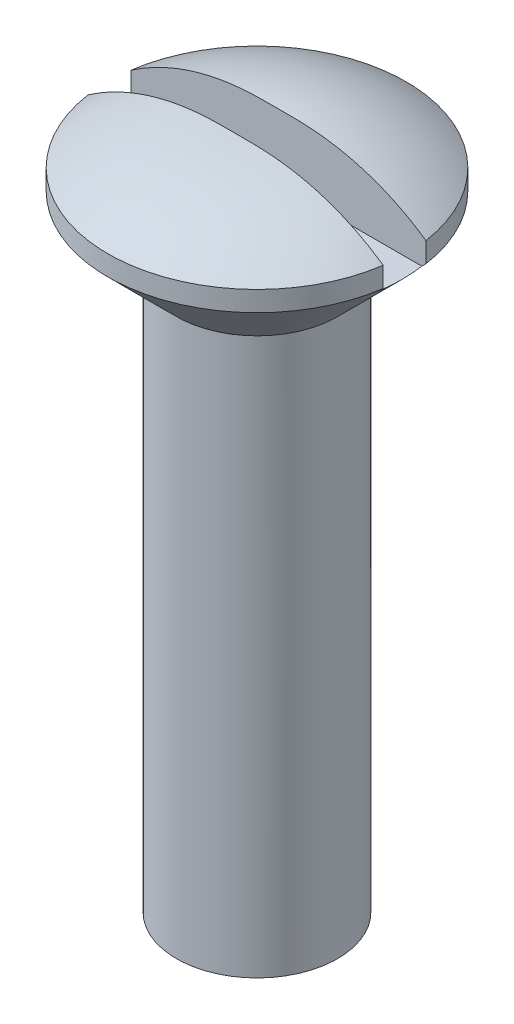
SolidWorks part; units mm, degrees
ref_plane "Спереди" through (0, 0, 0) normal (0, 0, 1) x (1, 0, 0)
ref_plane "Сверху" through (0, 0, 0) normal (0, 1, 0) x (1, 0, 0)
ref_plane "Справа" through (0, 0, 0) normal (1, 0, 0) x (0, 0, -1)
sketch "Эскиз1" plane through (0, 0, 0) normal (0, 0, 1) x (1, 0, 0)
  line L0 (0, 0) -> (0, 8.0477) construction
  line L1 (0, 0) -> (2, 0)
  line L2 (2, 0) -> (2, 13.8)
  line L3 (2, 13.8) -> (3.7, 15.5)
  line L4 (3.7, 15.5) -> (3.7, 16)
  line L5 (0, 17) -> (0.53, 17)
  line L6 (0, 0) -> (0, 17)
  arc A0 (0.53, 17) -> (3.7, 16) centre (0.53, 11.4756) cw
  dimension "D1" = 4
  dimension "D2" = 45
  dimension "D3" = 7.4
  dimension "D4" = 2.2
  dimension "D5" = 16
  dimension "D6" = 1
  dimension "D7" = 1.06
revolve "Основание-Повернуть" add sketch "Эскиз1" angle 360 about L0
sketch "Эскиз2" plane through (0, 17, 0) normal (0, 1, 0) x (-1, 0, 0)
  line L0 (-3.6618, -0.53) -> (3.6618, -0.53)
  line L1 (-3.6618, 0.53) -> (3.6618, 0.53)
  circle A0 centre (0, 0) radius 3.7 construction
  arc A1 (-3.6618, 0.53) -> (-3.6618, -0.53) centre (0, 0) ccw
  circle A2 centre (0, 0) radius 0.53 construction
  arc A3 (3.6618, -0.53) -> (3.6618, 0.53) centre (0, 0) ccw
extrude "Вырез-Вытянуть1" cut sketch "Эскиз2" against normal blind 1.6
